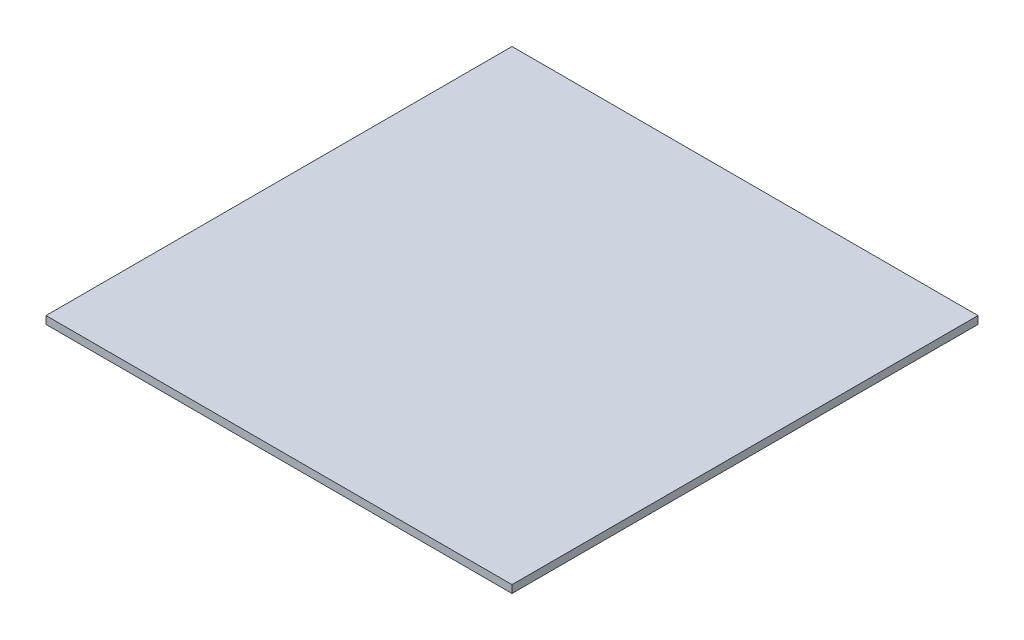
SolidWorks part; units mm, degrees
ref_plane "Front Plane" through (0, 0, 0) normal (0, 0, 1) x (1, 0, 0)
ref_plane "Top Plane" through (0, 0, 0) normal (0, 1, 0) x (1, 0, 0)
ref_plane "Right Plane" through (0, 0, 0) normal (1, 0, 0) x (0, 0, -1)
sketch "Sketch1" plane through (0, 0, 0) normal (0, 1, 0) x (1, 0, 0)
  line L1 (0, 0) -> (307.0225, 0)
  line L2 (0, 0) -> (0, 307.0225)
  line L3 (0, 307.0225) -> (307.0225, 307.0225)
  line L4 (307.0225, 0) -> (307.0225, 307.0225)
  dimension "D1" = 307.0225
extrude "Boss-Extrude1" add sketch "Sketch1" along normal blind 5.08
